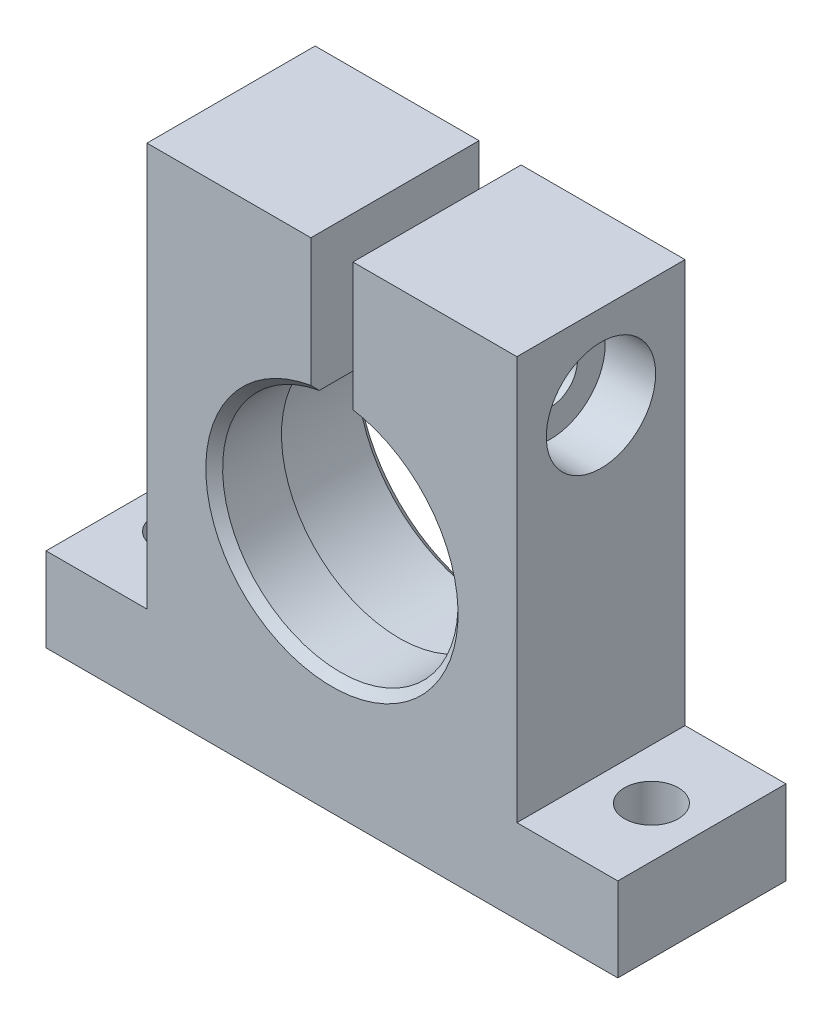
SolidWorks part; units mm, degrees
material "AISI 1045 Steel, cold drawn"
ref_plane "Front Plane" through (0, 0, 0) normal (0, 0, 1) x (1, 0, 0)
ref_plane "Top Plane" through (0, 0, 0) normal (0, 1, 0) x (1, 0, 0)
ref_plane "Right Plane" through (0, 0, 0) normal (1, 0, 0) x (0, 0, -1)
sketch "Sketch1" plane through (0, 0, 0) normal (0, 0, 1) x (1, 0, 0)
  line L1 (11, -14) -> (-11, -14)
  line L2 (11, -14) -> (11, 15)
  line L3 (11, 15) -> (-11, 15)
  line L4 (-11, -14) -> (-11, 15)
  line L5 (11, -14) -> (-11, 15) construction
  line L6 (11, 15) -> (-11, -14) construction
  circle A0 centre (0, 0) radius 8 construction
  point P3 (0, 0.5)
  point P8 (0, -12.3187)
  point P9 (0, 0)
  dimension "D1" = 16
  dimension "D2" = 29
  dimension "D3" = 15
  dimension "D4" = 22
extrude "Boss-Extrude1" add sketch "Sketch1" along normal mid plane 10
sketch "Sketch3" plane through (0, -14, 0) normal (0, -1, 0) x (1, 0, 0)
  line L0 (-11, 5) -> (11, 5) construction
  line L1 (17, -5) -> (-17, -5)
  line L2 (17, -5) -> (17, 5)
  line L3 (17, 5) -> (-17, 5)
  line L4 (-17, -5) -> (-17, 5)
  line L5 (17, -5) -> (-17, 5) construction
  line L6 (17, 5) -> (-17, -5) construction
  point P0 (0, 0)
  dimension "D1" = 34
extrude "Boss-Extrude2" add sketch "Sketch3" against normal blind 5
hole_wizard "Ø16.0 (16) Diameter Hole1" positions "Sketch4" profile "Sketch5" hole size "Ø16.0" standard "ANSI Metric"
sketch "Sketch4" plane through (0, 0, -5) normal (0, 0, -1) x (-1, 0, 0)
  point P0 (0, 0)
sketch "Sketch5" plane through (0, 0, -5) normal (1, 0, 0) x (0, 1, 0)
  line L0 (0, 0) -> (0, 6)
  line L1 (0, 6) -> (8, 6)
  line L2 (8, 6) -> (8, 0)
  line L5 (8, 0) -> (0, 0)
  line L10 (0, 6) -> (-8, 6) construction
  line L11 (0, -6.35) -> (0, 107.95) construction
  dimension "Hole Dia." = 16
  dimension "Hole Depth" = 6
  dimension "Drill Angle" = 180
hole_wizard "Ø14.0 (14) Diameter Hole1" positions "Sketch13" profile "Sketch14" hole size "Ø14.0" standard "ANSI Metric" end condition through all
sketch "Sketch13" plane through (0, 0, 1) normal (0, 0, -1) x (-1, 0, 0)
  point P0 (0, 0)
sketch "Sketch14" plane through (0, 0, 1) normal (1, 0, 0) x (0, 1, 0)
  line L0 (0, 0) -> (0, 4)
  line L1 (0, 4) -> (7, 4)
  line L2 (7, 4) -> (7, 0)
  line L5 (7, 0) -> (0, 0)
  line L11 (0, -6.35) -> (0, 107.95) construction
  dimension "Thru Hole Dia." = 14
  dimension "Thru Hole Depth" = 4
hole_wizard "M3 Clearance Hole1" positions "Sketch6" profile "Sketch7" hole size "M3" standard "ANSI Metric" end condition through all
sketch "Sketch6" plane through (0, -9, 0) normal (0, 1, 0) x (1, 0, 0)
  line L0 (-17, -5) -> (-11, 5) construction
  line L2 (17, -5) -> (11, 5) construction
  point P0 (-14, 0)
  point P2 (14, 0)
  point P17 (19.5, 0)
  point P18 (-19.5, 0)
sketch "Sketch7" plane through (-14, -9, 0) normal (1, 0, 0) x (0, 0, 1)
  line L0 (0, 0) -> (0, 5)
  line L1 (0, 5) -> (1.6, 5)
  line L2 (1.6, 5) -> (1.6, 0)
  line L5 (1.6, 0) -> (0, 0)
  line L11 (0, -6.35) -> (0, 107.95) construction
  dimension "Thru Hole Dia." = 3.2
  dimension "Thru Hole Depth" = 5
sketch "Sketch12" plane through (0, 0, 5) normal (0, 0, 1) x (1, 0, 0)
  line L0 (11, 15) -> (-11, 15) construction
  line L1 (1.25, 6.8875) -> (-1.25, 6.8875)
  line L2 (1.25, 6.8875) -> (1.25, 15)
  line L3 (1.25, 15) -> (-1.25, 15)
  line L4 (-1.25, 6.8875) -> (-1.25, 15)
  line L5 (1.25, 6.8875) -> (-1.25, 15) construction
  line L6 (1.25, 15) -> (-1.25, 6.8875) construction
  circle A1 centre (0, 0) radius 7 construction
  point P0 (0, 10.9437)
  point P7 (0, 0)
  point P9 (1.25, 7.9017)
  point P10 (1.25, 6.8875)
  dimension "D1" = 2.5
extrude "Cut-Extrude1" cut sketch "Sketch12" against normal through all
hole_wizard "M3x0.5 Tapped Hole1" positions "Sketch8" profile "Sketch9" tap size "M3x0.5" standard "ANSI Metric"
sketch "Sketch8" plane through (-11, 0, 0) normal (-1, 0, 0) x (0, 0, 1)
  line L0 (5, 15) -> (-5, 15) construction
  point P0 (0, 10)
  point P3 (0, 0)
  dimension "D1" = 5
sketch "Sketch9" plane through (-11, 10, 0) normal (0, 1, 0) x (0, 0, 1)
  line L0 (0, 0) -> (0, 9.75)
  line L1 (0, 9.75) -> (1.25, 9.75)
  line L2 (1.25, 9.75) -> (1.25, 0)
  line L5 (1.25, 0) -> (0, 0)
  line L11 (0, -6.35) -> (0, 107.95) construction
  dimension "Thru Tap Drill Dia." = 2.5
  dimension "Thru Tap Drill Depth" = 9.75
cosmetic thread "Hole Thread1" parameters "D2"=3
hole_wizard "CBORE for M3 SHCS1" positions "Sketch10" profile "Sketch11" counterbore size "M3" standard "ANSI Metric"
sketch "Sketch10" plane through (11, 0, 0) normal (1, 0, 0) x (0, 0, -1)
  point P0 (0, 10)
sketch "Sketch11" plane through (11, 10, 0) normal (0, 1, 0) x (0, 0, -1)
  line L0 (0, 0) -> (0, 9.75)
  line L1 (0, 9.75) -> (1.6, 9.75)
  line L3 (1.6, 9.75) -> (1.6, 3)
  line L4 (1.6, 3) -> (3.25, 3)
  line L5 (3.25, 3) -> (3.25, 0)
  line L7 (3.25, 0) -> (0, 0)
  line L11 (0, -6.35) -> (0, 107.95) construction
  dimension "Thru Hole Dia." = 3.2
  dimension "Thru Hole Depth" = 9.75
  dimension "C'Bore Dia." = 6.5
  dimension "C'Bore Depth" = 3
chamfer "Chamfer1" distance 0.5 angle 45 3 edges at (0, -8, -5) (0, -7, 5) (-11, 10, 1.25)
